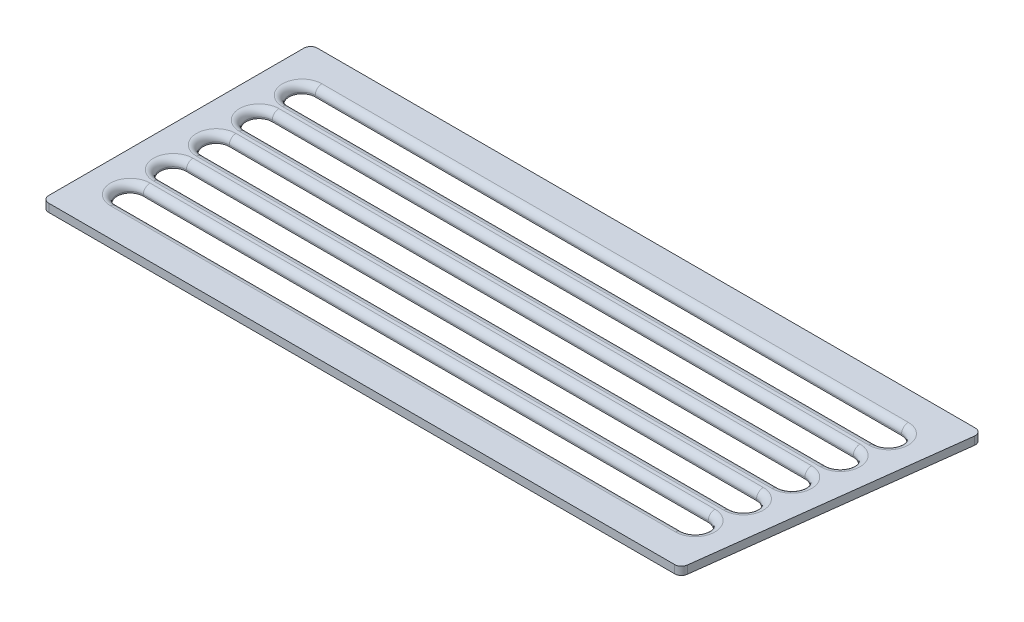
SolidWorks part; units mm, degrees
ref_plane "Front Plane" through (0, 0, 0) normal (0, 0, 1) x (1, 0, 0)
ref_plane "Top Plane" through (0, 0, 0) normal (0, 1, 0) x (1, 0, 0)
ref_plane "Right Plane" through (0, 0, 0) normal (1, 0, 0) x (0, 0, -1)
sketch "Sketch11" plane through (0, 0, 0) normal (0, 1, 0) x (1, 0, 0)
  line L0 (0, 50) -> (244, 50) construction
  line L8 (250.25, 100) -> (0, 100)
  line L9 (0, 100) -> (0, 0)
  line L10 (0, 0) -> (237.75, 0)
  line L11 (237.75, 0) -> (250.25, 100)
  line L15 (-2.2085, 167.5) -> (232.7915, 167.5) construction
  line L16 (-2.2085, 167.5) -> (-2.2085, -67.5) construction
  line L17 (-2.2085, -67.5) -> (232.7915, -67.5) construction
  line L18 (232.7915, 167.5) -> (232.7915, -67.5) construction
  line L19 (-2.2085, 167.5) -> (232.7915, -67.5) construction
  line L20 (-2.2085, -67.5) -> (232.7915, 167.5) construction
  point P2 (115.2915, 50)
  dimension "D1" = 100
  dimension "D2" = 244
  dimension "D3" = 97.125
  dimension "D4" = 235
  dimension "D5" = 235
  dimension "D6" = 17.4585
extrude "Boss-Extrude1" add sketch "Sketch11" along normal blind 3
sketch "Sketch12" plane through (0, 3, 0) normal (0, 1, 0) x (1, 0, 0)
  line L0 (14.85, 54.85) -> (229.15, 45.15) construction
  line L1 (0, 50) -> (244, 50) construction
  line L3 (10, 100) -> (10, 0) construction
  line L4 (0, 100) -> (0, 0) construction
  line L5 (237.75, 0) -> (250.25, 100) construction
  line L8 (227.8208, 0.2644) -> (240.3208, 100.2644) construction
  line L37 (14.85, 38.85) -> (227.15, 38.85)
  line L40 (14.85, 86.85) -> (233.15, 86.85)
  line L46 (14.85, 70.85) -> (231.15, 70.85)
  line L47 (14.85, 13.15) -> (225.15, 13.15)
  line L48 (14.85, 77.15) -> (233.15, 77.15)
  line L51 (14.85, 54.85) -> (229.15, 54.85)
  line L57 (14.85, 22.85) -> (225.15, 22.85)
  line L59 (14.85, 45.15) -> (229.15, 45.15)
  line L61 (14.85, 29.15) -> (227.15, 29.15)
  line L63 (14.85, 61.15) -> (231.15, 61.15)
  arc A13 (14.85, 22.85) -> (14.85, 13.15) centre (14.85, 18) ccw
  arc A14 (14.85, 38.85) -> (14.85, 29.15) centre (14.85, 34) ccw
  arc A15 (14.85, 54.85) -> (14.85, 45.15) centre (14.85, 50) ccw
  arc A16 (14.85, 70.85) -> (14.85, 61.15) centre (14.85, 66) ccw
  arc A17 (14.85, 86.85) -> (14.85, 77.15) centre (14.85, 82) ccw
  arc A18 (225.15, 13.15) -> (225.15, 22.85) centre (225.15, 18) ccw
  arc A19 (227.15, 29.15) -> (227.15, 38.85) centre (227.15, 34) ccw
  arc A20 (229.15, 45.15) -> (229.15, 54.85) centre (229.15, 50) ccw
  arc A21 (231.15, 61.15) -> (231.15, 70.85) centre (231.15, 66) ccw
  arc A22 (233.15, 77.15) -> (233.15, 86.85) centre (233.15, 82) ccw
  point P3 (10, 50)
  point P11 (234, 50)
  point P15 (122, 50)
  point P27 (10, 82)
  point P36 (238, 82)
  dimension "D1" = 9.7
  dimension "D2" = 6.3
  dimension "D3" = 6.3
  dimension "D4" = 6.3
  dimension "D5" = 6.3
  dimension "D7" = 228
  dimension "D6" = 224
extrude "Cut-Extrude1" cut sketch "Sketch12" against normal through all
fillet "Fillet1" radius 2.5 20 edges at (230, 3, -18) (120, 3, -13.15) (10, 3, -18) (232, 3, -34) (121, 3, -29.15) (10, 3, -34) (234, 3, -50) (122, 3, -45.15) (10, 3, -50) (236, 3, -66) (123, 3, -61.15) (10, 3, -66) (10, 3, -82) (124, 3, -86.85) (238, 3, -82) (120, 3, -22.85) (121, 3, -38.85) (122, 3, -54.85) (123, 3, -70.85) (124, 3, -77.15)
fillet "Fillet3" radius 2.5 4 edges at (0, 1.5, -100) (0, 1.5, 0) (250.25, 1.5, -100) (237.75, 1.5, 0)
sketch "Sketch13" plane through (0, 3, 0) normal (0, 1, 0) x (-1, 0, 0)
